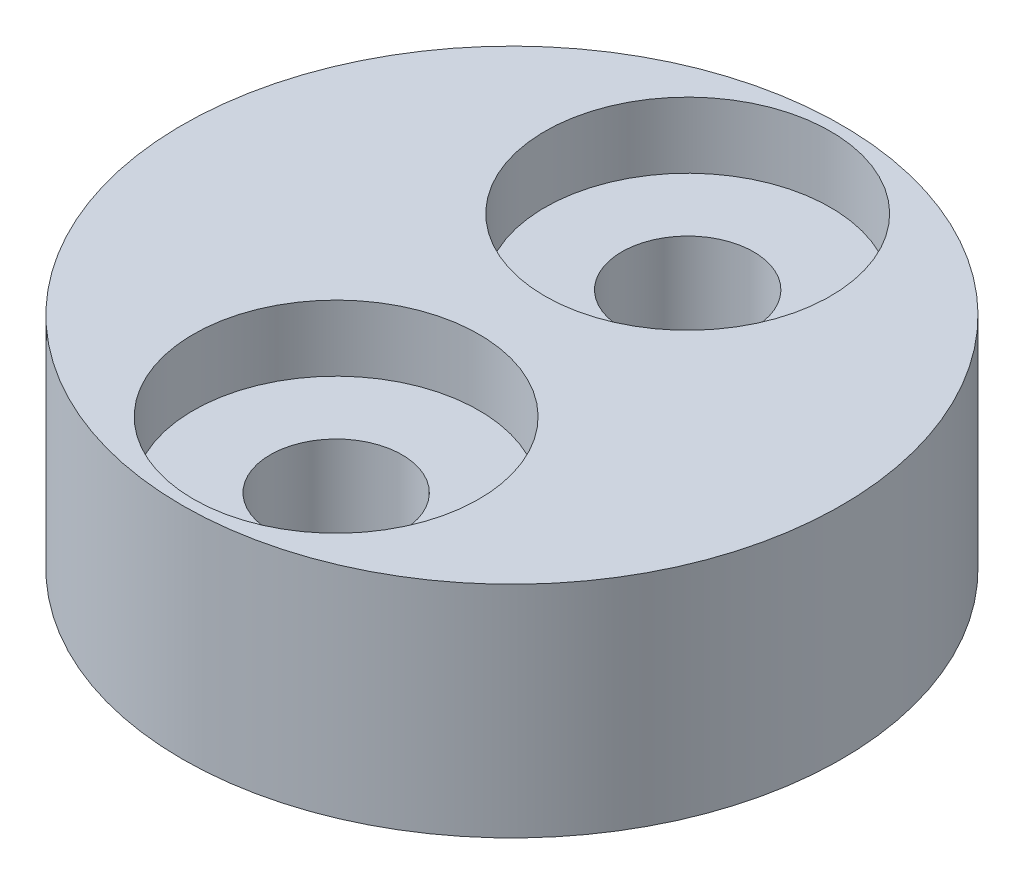
SolidWorks part; units mm, degrees
ref_plane "Front Plane" through (0, 0, 0) normal (0, 0, 1) x (1, 0, 0)
ref_plane "Top Plane" through (0, 0, 0) normal (0, 1, 0) x (1, 0, 0)
ref_plane "Right Plane" through (0, 0, 0) normal (1, 0, 0) x (0, 0, -1)
sketch "Sketch1" plane through (0, 0, 0) normal (0, 1, 0) x (1, 0, 0)
  circle A0 centre (0, 0) radius 7.5
  circle A1 centre (0, 0) radius 4 construction
  circle A3 centre (0, 4) radius 1.5
  circle A4 centre (0, -4) radius 1.5
  dimension "D1" = 15
  dimension "D2" = 8
  dimension "D3" = 3
extrude "Boss-Extrude1" add sketch "Sketch1" along normal blind 5
sketch "Sketch2" plane through (0, 5, 0) normal (0, 1, 0) x (1, 0, 0)
  circle A2 centre (0, 0) radius 4 construction
  circle A3 centre (0, 4) radius 3.25
  circle A4 centre (0, -4) radius 3.25
  point P2 (0, 0)
  point P7 (0, 0)
  point P12 (0, 0)
  dimension "D1" = 8
  dimension "D2" = 6.5
  dimension "D3" = 2
extrude "Cut-Extrude1" cut sketch "Sketch2" against normal blind 1.5
